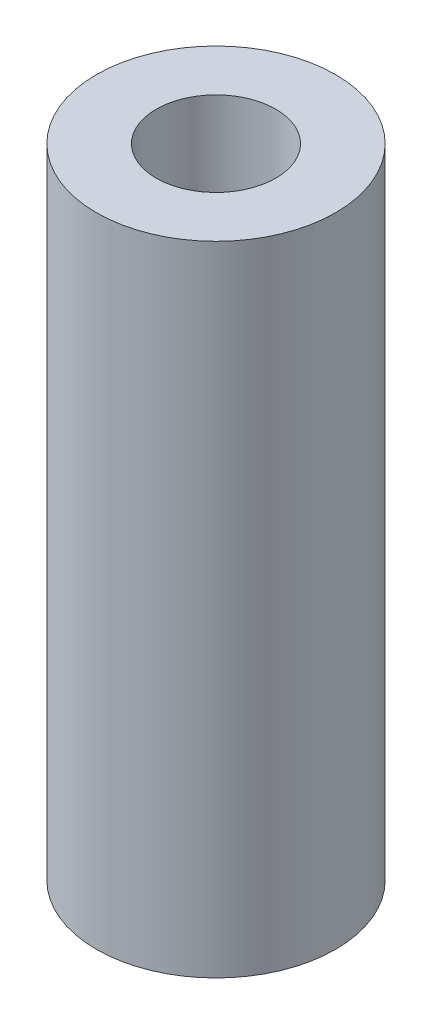
SolidWorks part; units mm, degrees
ref_plane "前视基准面" through (0, 0, 0) normal (0, 0, 1) x (1, 0, 0)
ref_plane "上视基准面" through (0, 0, 0) normal (0, 1, 0) x (1, 0, 0)
ref_plane "右视基准面" through (0, 0, 0) normal (1, 0, 0) x (0, 0, -1)
sketch "草图1" plane through (0, 0, 0) normal (0, 1, 0) x (1, 0, 0)
  circle A0 centre (0, 0) radius 1.5
  circle A1 centre (0, 0) radius 3
extrude "凸台-拉伸1" add sketch "草图1" along normal blind 16
